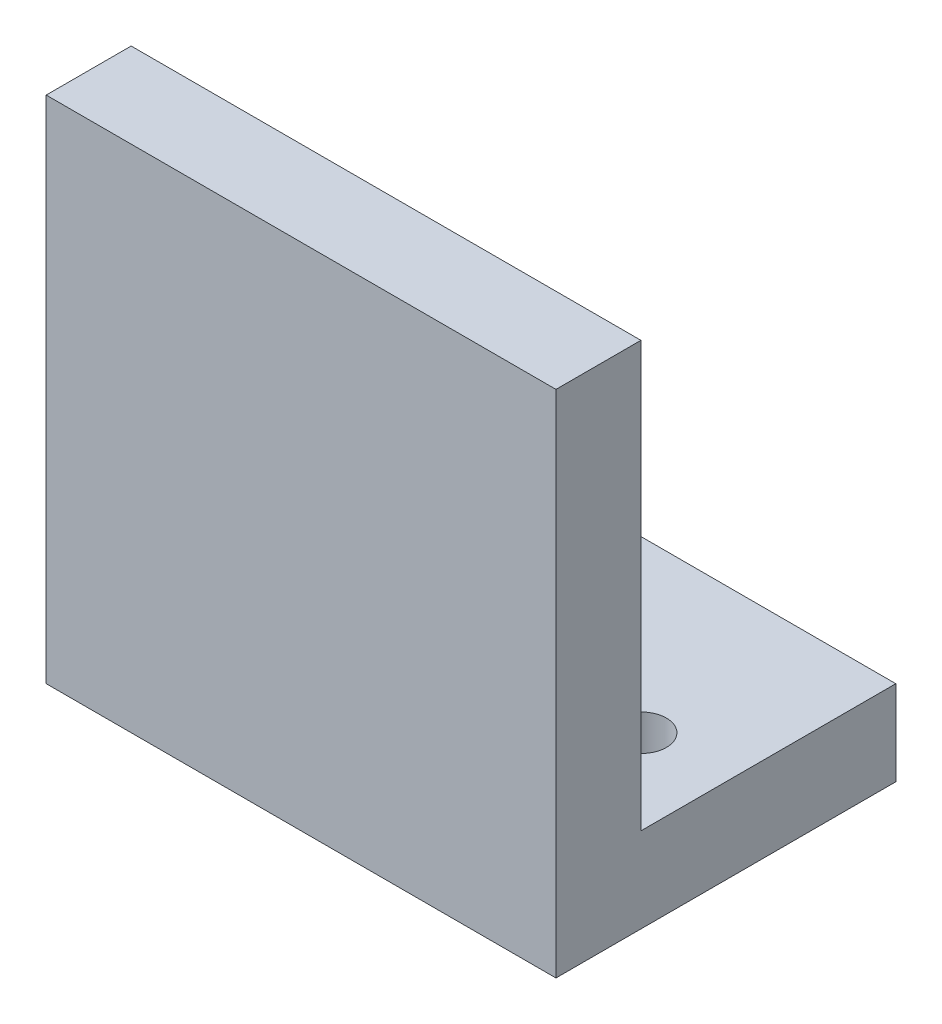
SolidWorks part; units mm, degrees
ref_plane "前视基准面" through (0, 0, 0) normal (0, 0, 1) x (1, 0, 0)
ref_plane "上视基准面" through (0, 0, 0) normal (0, 1, 0) x (1, 0, 0)
ref_plane "右视基准面" through (0, 0, 0) normal (1, 0, 0) x (0, 0, -1)
sketch "草图1" plane through (0, 0, 0) normal (1, 0, 0) x (0, 0, -1)
  line L0 (0, 25) -> (0, 0)
  line L1 (0, 0) -> (15, 0)
  line L2 (15, 0) -> (15, -5)
  line L3 (15, -5) -> (-5, -5)
  line L4 (-5, -5) -> (-5, 25)
  line L5 (-5, 25) -> (0, 25)
  dimension "D1" = 5
  dimension "D2" = 5
  dimension "D3" = 20
  dimension "D4" = 30
extrude "凸台-拉伸1" add sketch "草图1" along normal blind 30
sketch "草图2" plane through (0, 0, 0) normal (0, 1, 0) x (1, 0, 0)
  line L0 (0, 15) -> (0, 0) construction
  line L1 (30, -5) -> (0, -5) construction
  circle A0 centre (5, 5) radius 1.5
  circle A1 centre (25, 5) radius 1.5
  dimension "D1" = 3
  dimension "D5" = 3
  dimension "D2" = 20
  dimension "D3" = 5
  dimension "D4" = 10
extrude "切除-拉伸1" cut sketch "草图2" against normal blind 20
